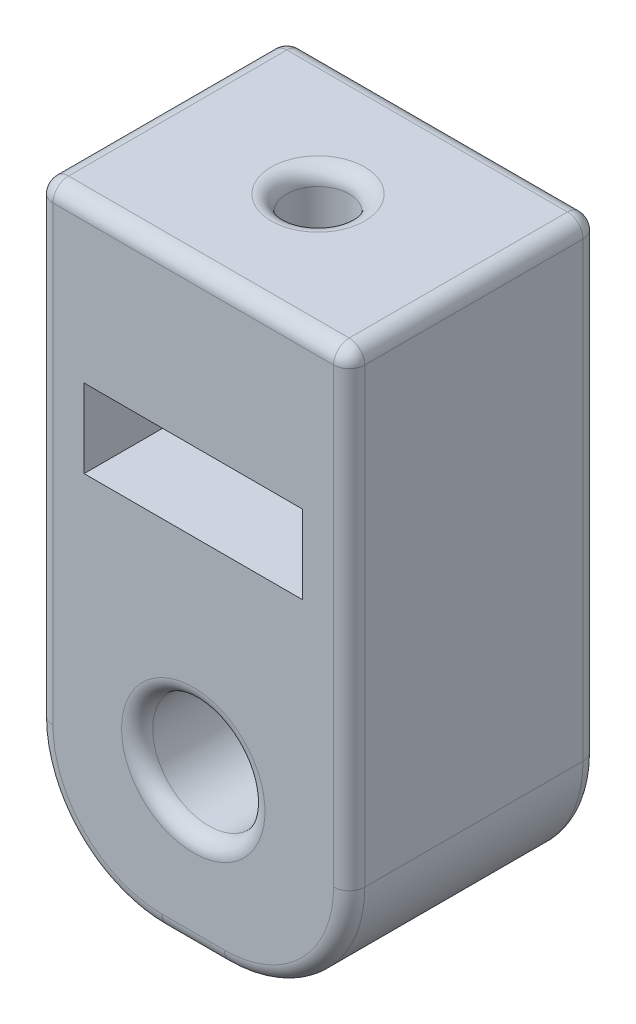
SolidWorks part; units mm, degrees
ref_plane "Front Plane" through (0, 0, 0) normal (0, 0, 1) x (1, 0, 0)
ref_plane "Top Plane" through (0, 0, 0) normal (0, 1, 0) x (1, 0, 0)
ref_plane "Right Plane" through (0, 0, 0) normal (1, 0, 0) x (0, 0, -1)
sketch "Sketch1" plane through (0, 0, 0) normal (0, 0, 1) x (1, 0, 0)
  line L1 (0, 0) -> (12.7, 0)
  line L2 (0, 0) -> (0, 24.13)
  line L3 (0, 24.13) -> (12.7, 24.13)
  line L4 (12.7, 0) -> (12.7, 24.13)
  circle A0 centre (6.35, 6.35) radius 2.286
  point P7 (6.35, 0)
  dimension "D2" = 4.572
  dimension "D1" = 24.13
  dimension "D3" = 6.35
  dimension "D4" = 12.7
extrude "Boss-Extrude1" add sketch "Sketch1" along normal blind 10.16
sketch "Sketch2" plane through (0, 24.13, 0) normal (0, 1, 0) x (1, 0, 0)
  line L0 (12.7, 0) -> (0, 0) construction
  line L1 (0, -10.16) -> (0, 0) construction
  circle A0 centre (6.35, -5.08) radius 1.27
  point P2 (6.35, 0)
  point P3 (0, -5.08)
  dimension "D1" = 2.54
extrude "Cut-Extrude1" cut sketch "Sketch2" against normal blind 15.24
fillet "Fillet2" radius 5.08 2 edges at (12.7, 0, 5.08) (0, 0, 5.08)
fillet "Fillet1" radius 0.635 17 edges at (8.636, 6.35, 0) (6.35, 0, 0) (0, 14.605, 0) (12.7, 14.605, 0) (12.7, 24.13, 5.08) (0, 24.13, 5.08) (6.35, 24.13, 0) (6.35, 24.13, 6.35) (8.636, 6.35, 10.16) (6.35, 24.13, 10.16) (12.7, 14.605, 10.16) (6.35, 0, 10.16) (0, 14.605, 10.16) (1.4879, 1.4879, 0) (11.2121, 1.4879, 0) (11.2121, 1.4879, 10.16) (1.4879, 1.4879, 10.16)
sketch "Sketch3" plane through (0, 0, 0) normal (0, 0, -1) x (-1, 0, 0)
  line L0 (-12.065, 24.13) -> (-0.635, 24.13) construction
  line L2 (-10.795, 17.78) -> (-1.905, 17.78)
  line L3 (-10.795, 17.78) -> (-10.795, 14.5847)
  line L4 (-10.795, 14.5847) -> (-1.905, 14.5847)
  line L5 (-1.905, 17.78) -> (-1.905, 14.5847)
  point P0 (-6.35, 24.13)
  point P7 (-6.35, 17.78)
  dimension "D1" = 6.35
  dimension "D2" = 3.1953
  dimension "D3" = 8.89
extrude "Cut-Extrude2" cut sketch "Sketch3" against normal through all
